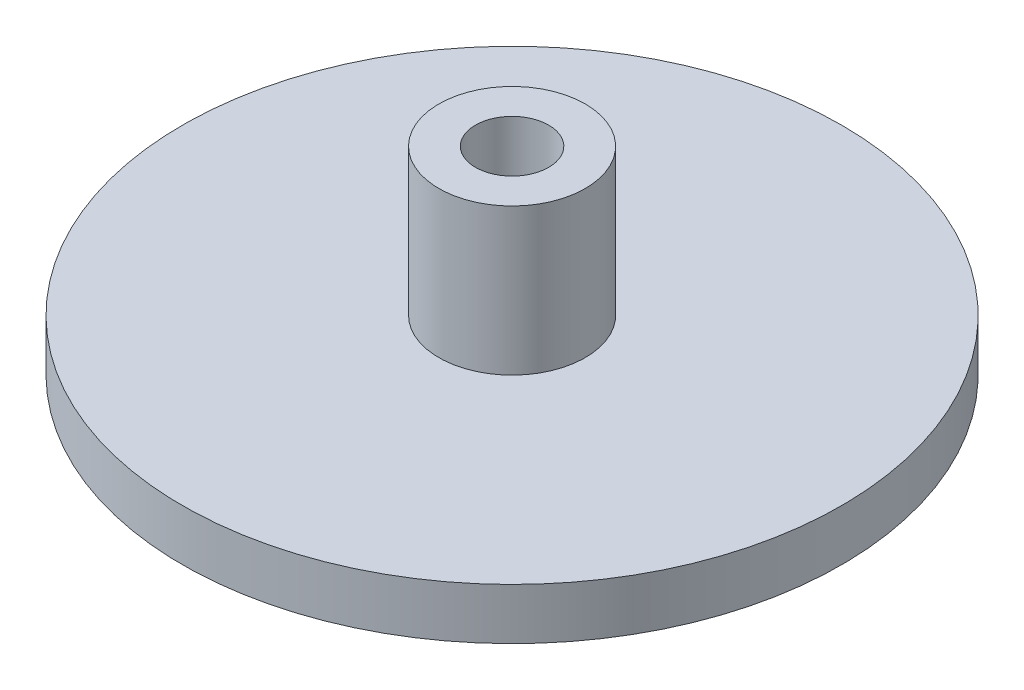
SolidWorks part; units mm, degrees
material "ABS"
ref_plane "Front Plane" through (0, 0, 0) normal (0, 0, 1) x (1, 0, 0)
ref_plane "Top Plane" through (0, 0, 0) normal (0, 1, 0) x (1, 0, 0)
ref_plane "Right Plane" through (0, 0, 0) normal (1, 0, 0) x (0, 0, -1)
sketch "Sketch1" plane through (0, 0, 0) normal (0, 0, 1) x (1, 0, 0)
  line L0 (0, 0) -> (0, 6.8676) construction
  line L1 (1, 0) -> (1, 5.4)
  line L2 (1, 5.4) -> (2, 5.4)
  line L3 (2, 5.4) -> (2, 1.4)
  line L4 (2, 1.4) -> (9, 1.4)
  line L5 (9, 1.4) -> (9, 0)
  line L6 (9, 0) -> (1, 0)
  point P5 (0, 6.8676)
  dimension "D1" = 1
  dimension "D2" = 9
  dimension "D3" = 2
  dimension "D4" = 1.4
  dimension "D5" = 4
revolve "Revolve1" add sketch "Sketch1" angle 360 about L0
